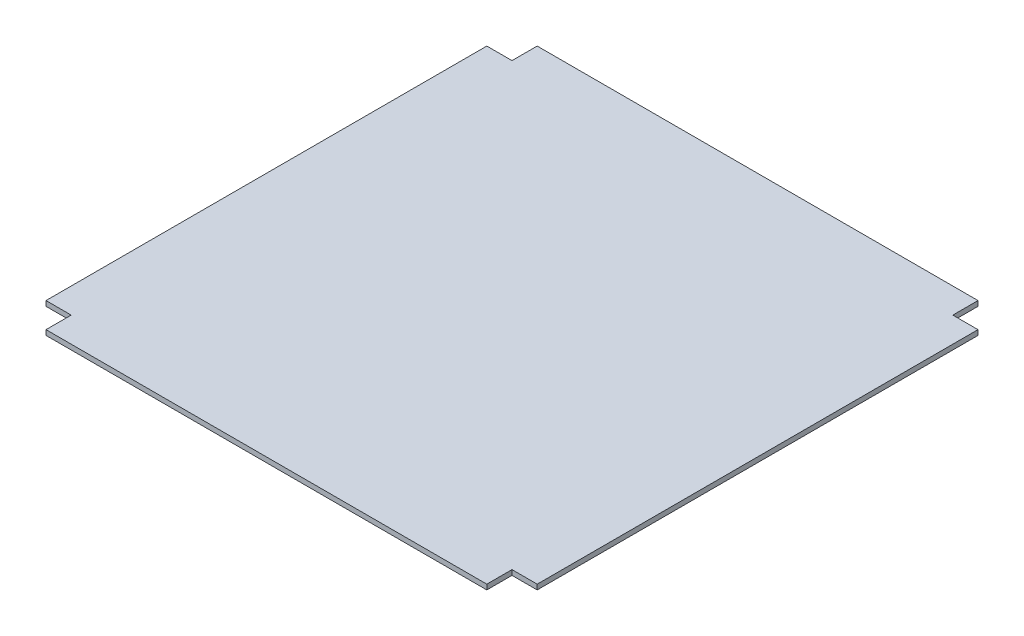
SolidWorks part; units mm, degrees
material "6061 Alloy"
ref_plane "Front Plane" through (0, 0, 0) normal (0, 0, 1) x (1, 0, 0)
ref_plane "Top Plane" through (0, 0, 0) normal (0, 1, 0) x (1, 0, 0)
ref_plane "Right Plane" through (0, 0, 0) normal (1, 0, 0) x (0, 0, -1)
sketch "Sketch1" plane through (0, 0, 0) normal (0, 1, 0) x (1, 0, 0)
  line L1 (195, -195) -> (-195, -195)
  line L2 (195, -195) -> (195, 195)
  line L3 (195, 195) -> (-195, 195)
  line L4 (-195, -195) -> (-195, 195)
  line L5 (195, -195) -> (-195, 195) construction
  line L6 (195, 195) -> (-195, -195) construction
  point P0 (0, 0)
  point P1 (0, 0)
  dimension "D1" = 390
extrude "Boss-Extrude1" add sketch "Sketch1" along normal blind 4
sketch "Sketch2" plane through (0, 4, 0) normal (0, 1, 0) x (1, 0, 0)
  line L0 (0, 0) -> (0, 195) construction
  line L1 (-195, 195) -> (-175, 195)
  line L2 (-195, 195) -> (-195, 175)
  line L3 (-195, 175) -> (-175, 175)
  line L4 (-175, 195) -> (-175, 175)
  line L5 (195, 195) -> (-195, 195) construction
  line L6 (175, 195) -> (175, 175)
  line L7 (195, -195) -> (195, 195) construction
  line L8 (195, 0) -> (0, 0) construction
  line L9 (195, 175) -> (175, 175)
  line L10 (195, 195) -> (195, 175)
  line L11 (195, 195) -> (175, 195)
  line L12 (195, -195) -> (175, -195)
  line L13 (195, -195) -> (195, -175)
  line L14 (195, -175) -> (175, -175)
  line L15 (175, -195) -> (175, -175)
  line L16 (-175, -195) -> (-175, -175)
  line L17 (-195, -175) -> (-175, -175)
  line L18 (-195, -195) -> (-195, -175)
  line L19 (-195, -195) -> (-175, -195)
  dimension "D1" = 20
  dimension "D2" = 20
extrude "Cut-Extrude1" cut sketch "Sketch2" against normal blind 10
